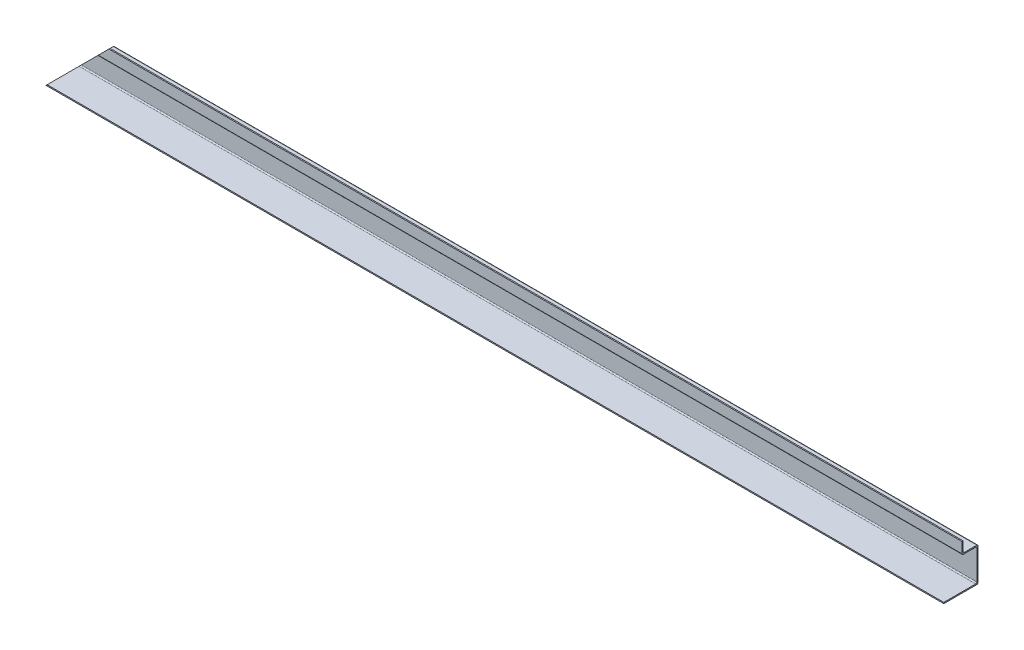
SolidWorks part; units mm, degrees
ref_plane "Front Plane" through (0, 0, 0) normal (0, 0, 1) x (1, 0, 0)
ref_plane "Top Plane" through (0, 0, 0) normal (0, 1, 0) x (1, 0, 0)
ref_plane "Right Plane" through (0, 0, 0) normal (1, 0, 0) x (0, 0, -1)
sketch "Sketch1" plane through (0, 0, 0) normal (1, 0, 0) x (0, 0, -1)
  line L0 (0, 0) -> (85, 0)
  line L1 (85, 0) -> (85, 82)
  line L2 (85, 82) -> (47, 82)
  line L3 (47, 82) -> (47, 112)
  line L4 (0, -3) -> (88, -3)
  line L5 (88, -3) -> (88, 85)
  line L6 (88, 85) -> (50, 85)
  line L7 (50, 85) -> (50, 112)
  line L8 (47, 112) -> (50, 112)
  line L9 (0, 0) -> (0, -3)
  point P11 (48.5, 112)
  dimension "D1" = 3
  dimension "D2" = 27
  dimension "D3" = 38
  dimension "D4" = 88
  dimension "D5" = 88
extrude "Boss-Extrude1" add sketch "Sketch1" along normal blind 2310
fillet "Fillet1" radius 3 6 edges at (1155, -3, -88) (1155, 85, -88) (1155, 85, -50) (1155, 82, -85) (1155, 0, -85) (1155, 82, -47)
sketch "Sketch2" plane through (0, 0, -88) normal (0, 0, -1) x (-1, 0, 0)
  line L0 (0, -3) -> (-115, 112)
  line L1 (-2310, 112) -> (0, 112) construction
  line L2 (-115, 112) -> (0, 112)
  line L3 (0, 112) -> (0, -3)
  dimension "D1" = 45
extrude "Cut-Extrude1" cut sketch "Sketch2" against normal blind 88
equation "\"D1@Boss-Extrude1\" = \"indoorHeight\" + \"indoorHeight_para\" + 80 + \"rearLightHeight_para\""
equation "\"CarBeamWidth\"=700.0"
equation "\"WheelWidth\"=650.0"
equation "\"Wheel_FrontBoxDistance\"=1390.0"
equation "\"boxLength\"=5100.0"
equation "\"boxWidth\"=1930.0"
equation "\"MetalSheet_3mm_length\"=5030.0"
equation "\"MetalSheet_3mm_width\"=1923.0"
equation "\"MetalSheet_3mm_FloorCut_L_length\"=1764.0"
equation "\"MetalSheet_3mm_FloorCut_L_disdance\"=1665.0"
equation "\"MetalSheet_3mm_FloorCut_R_length\"=1764.0"
equation "\"MetalSheet_3mm_FloorCut_R_disdance\"=1665.0"
equation "\"indoorHeight\"=1940.0"
equation "\"indoorHeight_para\"=25.0"
equation "\"rearLightHeight_para\"=265.0"
equation "\"haveDoor_R\"=1"
equation "\"side_door_bottom_R_3mm_length\"=1934.0"
equation "\"side_door_bottom_R_3mm_toFrontDistance\"=1583.0"
equation "\"1Bar_Side_RF_3mm_length\"=1493.0"
equation "\"1Bar_Side_RB_3mm_length\"=1493.0"
equation "\"DoorSeparator_RF_3mm_withHinge_toFrontDistance\"=1673.0"
equation "\"DoorSeparator_RF_3mm_withHinge_exist\"=1"
equation "\"DoorSeparator_RB_3mm_withHinge_toFrontDistance\"=3427.0"
equation "\"DoorSeparator_RB_3mm_withHinge_exist\"=1"
equation "\"Door_R1_L_open_Single_toFrontDistance\"=2547.5"
equation "\"Door_R1_L_open_Single_exist\"=1"
equation "\"door_base_long7_R1_L_open_Single_height\"=1890.0"
equation "\"door_base_short7_R1_L_open_Single_height\"=1890.0"
equation "\"door_base_short7_R1_L_open_Single_width\"=864"
equation "\"Door_R1_R_open_Single_toFrontDistance\"=3422.0"
equation "\"Door_R1_R_open_Single_exist\"=1"
equation "\"door_base_long7_R1_R_open_Single_height\"=1890.0"
equation "\"door_base_short7_R1_R_open_Single_height\"=1890.0"
equation "\"door_base_short7_R1_R_open_Single_width\"=864"
equation "\"x\"=66.0"
equation "\"da\"=62.0"
equation "\"SquareTube_length\"=1923.0"
equation "\"channelSteel_length\"=5030.0"
equation "\"SquareTube_inFront_AvgDistance\"=285.0"
equation "\"SquareTube_inFront_TotalCount\"=5"
equation "\"SquareTube_inFront1_cutDepth50_R\"=0.5"
equation "\"SquareTube_inFront1_cutDepth50_L\"=0.5"
equation "\"SquareTube_inFront2_cutDepth50_R\"=0.5"
equation "\"SquareTube_inFront2_cutDepth50_L\"=0.5"
equation "\"SquareTube_inFront3_cutDepth50_R\"=0.5"
equation "\"SquareTube_inFront3_cutDepth50_L\"=0.5"
equation "\"SquareTube_inFront4_cutDepth50_R\"=0.5"
equation "\"SquareTube_inFront4_cutDepth50_L\"=0.5"
equation "\"SquareTube_inFront5_cutDepth50_R\"=50"
equation "\"SquareTube_inFront5_cutDepth50_L\"=50"
equation "\"SquareTube_inFront6_cutDepth50_R\"=50"
equation "\"SquareTube_inFront6_cutDepth50_L\"=50"
equation "\"SquareTube_inFront7_cutDepth50_R\"=50"
equation "\"SquareTube_inFront7_cutDepth50_L\"=50"
equation "\"SquareTube_inFront8_cutDepth50_R\"=50"
equation "\"SquareTube_inFront8_cutDepth50_L\"=50"
equation "\"SquareTube_inFront9_cutDepth50_R\"=50"
equation "\"SquareTube_inFront9_cutDepth50_L\"=50"
equation "\"SquareTube_inFront10_cutDepth50_R\"=50"
equation "\"SquareTube_inFront10_cutDepth50_L\"=50"
equation "\"SquareTube_inFront11_cutDepth50_R\"=50"
equation "\"SquareTube_inFront11_cutDepth50_L\"=50"
equation "\"SquareTube_inFront12_cutDepth50_R\"=50"
equation "\"SquareTube_inFront12_cutDepth50_L\"=50"
equation "\"SquareTube_inFront13_cutDepth50_R\"=50"
equation "\"SquareTube_inFront13_cutDepth50_L\"=50"
equation "\"SquareTube_inFront14_cutDepth50_R\"=50"
equation "\"SquareTube_inFront14_cutDepth50_L\"=50"
equation "\"SquareTube_inBack_AvgDistance\"=333.125"
equation "\"SquareTube_inBack_TotalCount\"=9"
equation "\"SquareTube_inBack1_cutDepth50_R\"=50"
equation "\"SquareTube_inBack1_cutDepth50_L\"=50"
equation "\"SquareTube_inBack2_cutDepth50_R\"=50"
equation "\"SquareTube_inBack2_cutDepth50_L\"=50"
equation "\"SquareTube_inBack3_cutDepth50_R\"=50"
equation "\"SquareTube_inBack3_cutDepth50_L\"=50"
equation "\"SquareTube_inBack4_cutDepth50_R\"=50"
equation "\"SquareTube_inBack4_cutDepth50_L\"=50"
equation "\"SquareTube_inBack5_cutDepth50_R\"=50"
equation "\"SquareTube_inBack5_cutDepth50_L\"=50"
equation "\"SquareTube_inBack6_cutDepth50_R\"=0.5"
equation "\"SquareTube_inBack6_cutDepth50_L\"=0.5"
equation "\"SquareTube_inBack7_cutDepth50_R\"=0.5"
equation "\"SquareTube_inBack7_cutDepth50_L\"=0.5"
equation "\"SquareTube_inBack8_cutDepth50_R\"=0.5"
equation "\"SquareTube_inBack8_cutDepth50_L\"=0.5"
